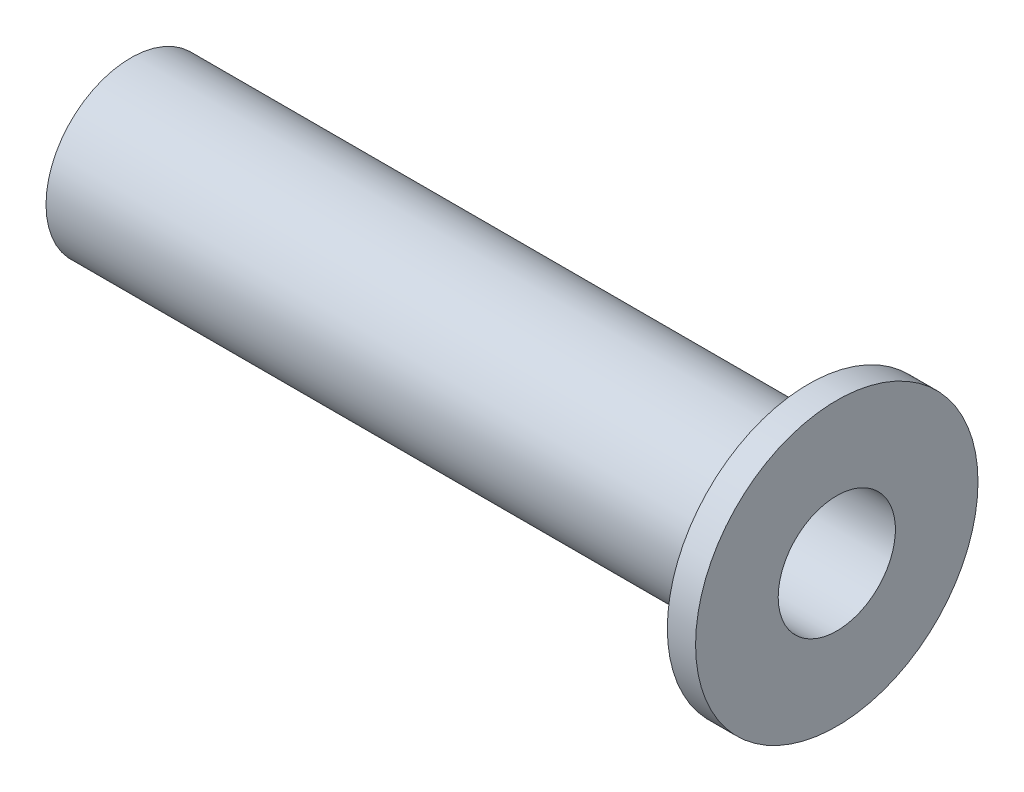
SolidWorks part; units mm, degrees
ref_plane "Front" through (0, 0, 0) normal (0, 0, 1) x (1, 0, 0)
ref_plane "Top" through (0, 0, 0) normal (0, 1, 0) x (1, 0, 0)
ref_plane "Right" through (0, 0, 0) normal (1, 0, 0) x (0, 0, -1)
sketch "Эскиз1" plane through (0, 0, 0) normal (0, 0, 1) x (1, 0, 0)
  line L0 (-92.8103, 0) -> (76.5339, 0) construction
  line L1 (-84.1527, 4.15) -> (-34.1527, 4.15)
  line L2 (-34.1527, 4.15) -> (-34.1527, 10)
  line L3 (-34.1527, 10) -> (-36.1527, 10)
  line L5 (-84.1527, 4.15) -> (-84.1527, 6)
  line L6 (-84.1527, 6) -> (-36.1527, 6)
  line L7 (-36.1527, 10) -> (-36.1527, 6)
  dimension "D1" = 8.3
  dimension "D2" = 12
  dimension "D3" = 20
  dimension "D4" = 50
  dimension "D5" = 2
revolve "Повернуть1" add sketch "Эскиз1" angle 360 about L0
